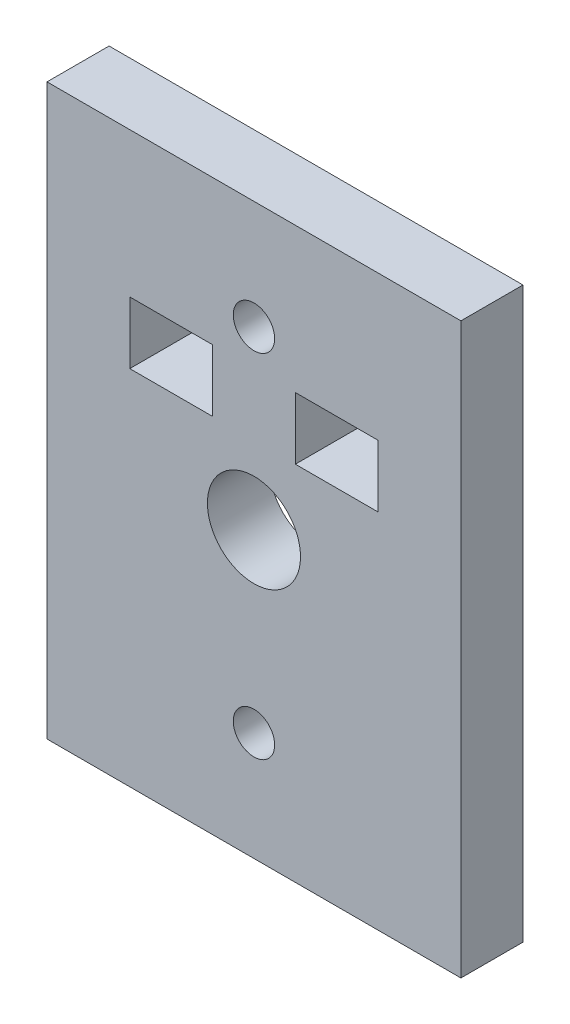
SolidWorks part; units mm, degrees
ref_plane "Alzado" through (0, 0, 0) normal (0, 0, 1) x (1, 0, 0)
ref_plane "Planta" through (0, 0, 0) normal (0, 1, 0) x (1, 0, 0)
ref_plane "Vista lateral" through (0, 0, 0) normal (1, 0, 0) x (0, 0, -1)
sketch "Croquis1" plane through (0, 0, 0) normal (0, 0, 1) x (1, 0, 0)
  line L0 (-10, -13.75) -> (-10, 13.75)
  line L1 (-10, -13.75) -> (10, -13.75)
  line L2 (-10, 13.75) -> (10, 13.75)
  line L3 (10, -13.75) -> (10, 13.75)
  line L4 (-10, -13.75) -> (10, 13.75) construction
  line L5 (-10, 13.75) -> (10, -13.75) construction
  line L18 (0, 0) -> (0, 8.8171) construction
  line L19 (6, 6.75) -> (2, 6.75)
  line L20 (-6, 3.75) -> (-2, 3.75)
  line L21 (-6, 3.75) -> (-6, 6.75)
  line L22 (-6, 6.75) -> (-2, 6.75)
  line L23 (-2, 3.75) -> (-2, 6.75)
  line L24 (2, 3.75) -> (2, 6.75)
  line L25 (6, 3.75) -> (2, 3.75)
  line L26 (6, 3.75) -> (6, 6.75)
  line L27 (0, 0) -> (6.2481, 0) construction
  circle A0 centre (0, 0) radius 2.25
  circle A1 centre (0, 8.5) radius 1
  circle A2 centre (0, -8.5) radius 1
  point P1 (0, 0)
  dimension "D7" = 4.5
  dimension "D8" = 2
  dimension "D1" = 20
  dimension "D2" = 3
  dimension "D3" = 4
  dimension "D4" = 27.5
  dimension "D6" = 7
  dimension "D5" = 4
  dimension "D9" = 8.5
extrude "Saliente-Extruir1" add sketch "Croquis1" along normal blind 3
